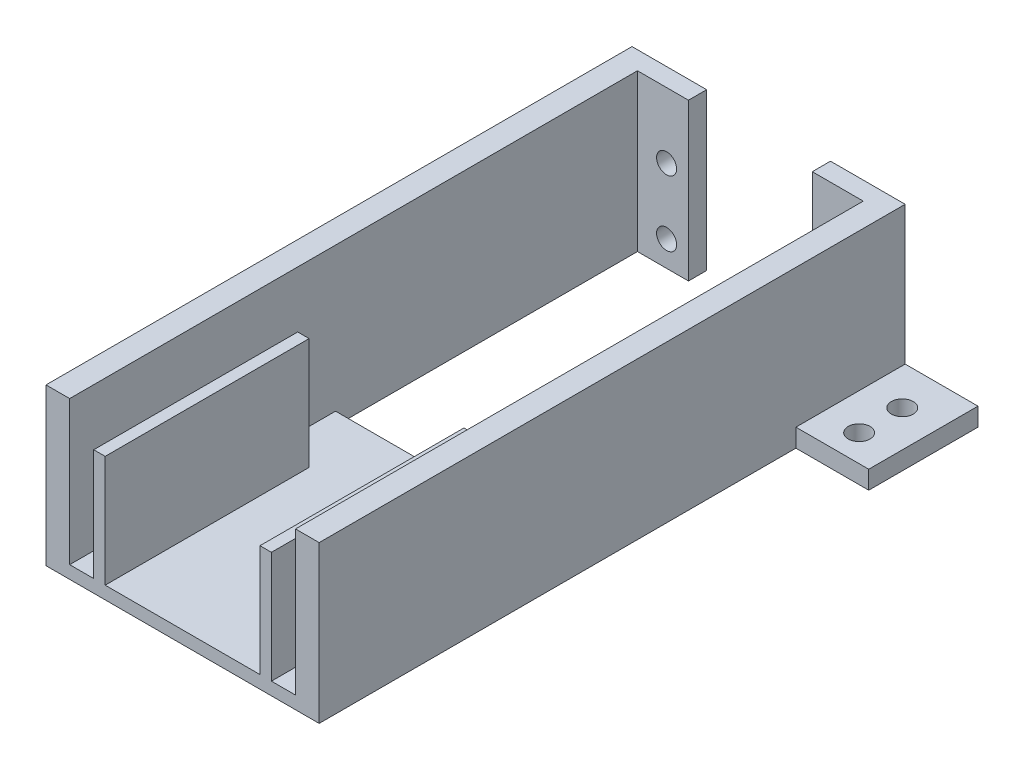
SolidWorks part; units mm, degrees
material "ABS"
ref_plane "Front Plane" through (0, 0, 0) normal (0, 0, 1) x (1, 0, 0)
ref_plane "Top Plane" through (0, 0, 0) normal (0, 1, 0) x (1, 0, 0)
ref_plane "Right Plane" through (0, 0, 0) normal (1, 0, 0) x (0, 0, -1)
sketch "Sketch1" plane through (0, 0, 0) normal (0, 0, 1) x (1, 0, 0)
  line L0 (20.5, 43) -> (20.5, 18)
  line L2 (0, 0) -> (0, 43)
  line L4 (75, 0) -> (75, 43)
  line L5 (0, 43) -> (20.5, 43)
  line L6 (54.5, 18) -> (54.5, 43)
  line L7 (37.5, 43) -> (37.5, 0) construction
  line L8 (0, 0) -> (20.5, 0)
  line L9 (20.5, 0) -> (20.5, 18)
  line L10 (54.5, 18) -> (54.5, 0)
  line L11 (54.5, 0) -> (75, 0)
  line L12 (54.5, 43) -> (75, 43)
  circle A0 centre (14.5, 25) radius 2.75
  circle A1 centre (14.5, 7) radius 2.75
  circle A2 centre (60.5, 7) radius 2.75
  circle A3 centre (60.5, 25) radius 2.75
  dimension "D6" = 5.5
  dimension "D7" = 46
  dimension "D8" = 34
  dimension "D1" = 43
  dimension "D2" = 75
  dimension "D3" = 17
  dimension "D4" = 18
  dimension "D10" = 14.5
  dimension "D11" = 6
extrude "Boss-Extrude1" add sketch "Sketch1" along normal blind 5
sketch "Sketch16" plane through (0, 0, 5) normal (0, 0, 1) x (1, 0, 0)
  line L0 (0, 41.7723) -> (6.5, 41.7723) construction
  line L1 (0, 0) -> (0, 43) construction
  line L2 (75, 41.0629) -> (68.5, 41.0629) construction
  line L3 (75, 0) -> (75, 43) construction
  line L4 (54.5, 43) -> (75, 43) construction
  line L5 (68.5, 43) -> (75, 43)
  line L6 (68.5, 43) -> (68.5, 0)
  line L7 (68.5, 0) -> (75, 0)
  line L8 (75, 43) -> (75, 0)
  line L9 (0, 43) -> (20.5, 43) construction
  line L10 (6.5, 43) -> (0, 43)
  line L11 (6.5, 43) -> (6.5, 0)
  line L12 (6.5, 0) -> (0, 0)
  line L13 (0, 43) -> (0, 0)
extrude "Boss-Extrude2" add sketch "Sketch16" along normal blind 162.9
sketch "Sketch18" plane through (68.5, 0, 0) normal (-1, 0, 0) x (0, 0, 1)
  line L0 (167.9, 0) -> (167.9, 3.5)
  line L1 (167.9, 43) -> (167.9, 0) construction
  line L2 (167.9, 3.5) -> (87.9, 3.5)
  line L3 (87.9, 3.5) -> (87.9, 0)
  line L4 (167.9, 0) -> (5, 0) construction
  line L5 (87.9, 0) -> (167.9, 0)
extrude "Boss-Extrude3" add sketch "Sketch18" along normal blind 64.9
sketch "Sketch19" plane through (68.5, 0, 0) normal (-1, 0, 0) x (0, 0, 1)
  line L0 (167.9, 3.5) -> (87.9, 3.5) construction
  line L1 (167.9, 43) -> (162.9, 43)
  line L2 (167.9, 43) -> (167.9, 3.5)
  line L3 (167.9, 3.5) -> (162.9, 3.5)
  line L4 (162.9, 43) -> (162.9, 3.5)
extrude "Boss-Extrude4" add sketch "Sketch19" along normal blind 64.9
sketch "Sketch20" plane through (0, 0, 0) normal (-1, 0, 0) x (0, 0, 1)
  line L1 (0, 0) -> (30, 0)
  line L2 (0, 0) -> (0, 5)
  line L3 (0, 5) -> (30, 5)
  line L4 (30, 0) -> (30, 5)
extrude "Boss-Extrude5" add sketch "Sketch20" along normal blind 20
sketch "Sketch21" plane through (75, 0, 0) normal (1, 0, 0) x (0, 0, -1)
  line L0 (-167.9, 0) -> (0, 0) construction
  line L1 (0, 5) -> (-30, 5)
  line L2 (0, 5) -> (0, 0)
  line L3 (0, 0) -> (-30, 0)
  line L4 (-30, 5) -> (-30, 0)
extrude "Boss-Extrude6" add sketch "Sketch21" along normal blind 20
sketch "Sketch22" plane through (0, 5, 0) normal (0, 1, 0) x (1, 0, 0)
  line L0 (-10, 0) -> (-10, -10.7991) construction
  line L1 (-20, 0) -> (0, 0) construction
  line L2 (85, 0) -> (85, -10.7991) construction
  line L3 (95, 0) -> (75, 0) construction
  line L4 (85, -10.7991) -> (85, -22.6338) construction
  line L5 (-10, -10.7991) -> (-10, -22.6338) construction
  circle A0 centre (-10, -10.7991) radius 3
  circle A1 centre (-10, -22.6338) radius 3
  circle A2 centre (85, -10.7991) radius 3
  circle A3 centre (85, -22.6338) radius 3
  dimension "D1" = 6
  dimension "D2" = 6
  dimension "D3" = 6
  dimension "D4" = 6
extrude "Cut-Extrude1" cut sketch "Sketch22" against normal blind 20
sketch "Sketch23" plane through (0, 0, 162.9) normal (0, 0, -1) x (-1, 0, 0)
sketch "Sketch24" plane through (0, 0, 162.9) normal (0, 0, -1) x (-1, 0, 0)
  line L0 (-37.5, 43) -> (-37.5, 3.5) construction
  line L1 (-6.5, 43) -> (-68.5, 43) construction
  line L2 (-6.5, 3.5) -> (-68.5, 3.5) construction
  line L3 (-37.5, 34.1387) -> (-16.25, 34.1387) construction
  line L4 (-37.5, 34.1387) -> (-58.75, 34.1387) construction
  line L10 (-58.75, 34.1387) -> (-61.8901, 34.1387)
  line L11 (-58.75, 34.1387) -> (-58.75, 3.5)
  line L12 (-58.75, 3.5) -> (-61.8901, 3.5)
  line L13 (-61.8901, 34.1387) -> (-61.8901, 3.5)
  line L14 (-16.25, 34.1387) -> (-13.11, 34.1387)
  line L15 (-16.25, 34.1387) -> (-16.25, 3.5)
  line L16 (-16.25, 3.5) -> (-13.11, 3.5)
  line L17 (-13.11, 34.1387) -> (-13.11, 3.5)
extrude "Boss-Extrude8" add sketch "Sketch24" along normal blind 58
sketch "Sketch25" plane through (0, 0, 167.9) normal (0, 0, 1) x (1, 0, 0)
  line L1 (0, 43) -> (75, 43)
  line L2 (0, 43) -> (0, 0)
  line L3 (0, 0) -> (75, 0)
  line L4 (75, 43) -> (75, 0)
extrude "Cut-Extrude2" cut sketch "Sketch25" against normal blind 7
sketch "Sketch15" plane through (0, 0, 0) normal (0, 0, -1) x (-1, 0, 0)
  line L0 (-54.5, 29.2278) -> (-75, 29.2278)
  line L1 (-54.5, 7.5) -> (-54.5, 32.5) construction
  line L2 (-75, 0) -> (-75, 32.5) construction
  line L3 (-75, 29.2278) -> (-75, 32.5)
  line L4 (-75, 32.5) -> (-54.5, 32.5)
  line L5 (-54.5, 32.5) -> (-54.5, 29.2278)
  line L6 (-20.5, 32.5) -> (-20.5, 29.2278)
  line L7 (-20.5, 32.5) -> (-20.5, 7.5) construction
  line L8 (-20.5, 29.2278) -> (0, 29.2278)
  line L9 (0, 0) -> (0, 32.5) construction
  line L10 (0, 29.2278) -> (0, 32.5)
  line L11 (0, 32.5) -> (-20.5, 32.5)
